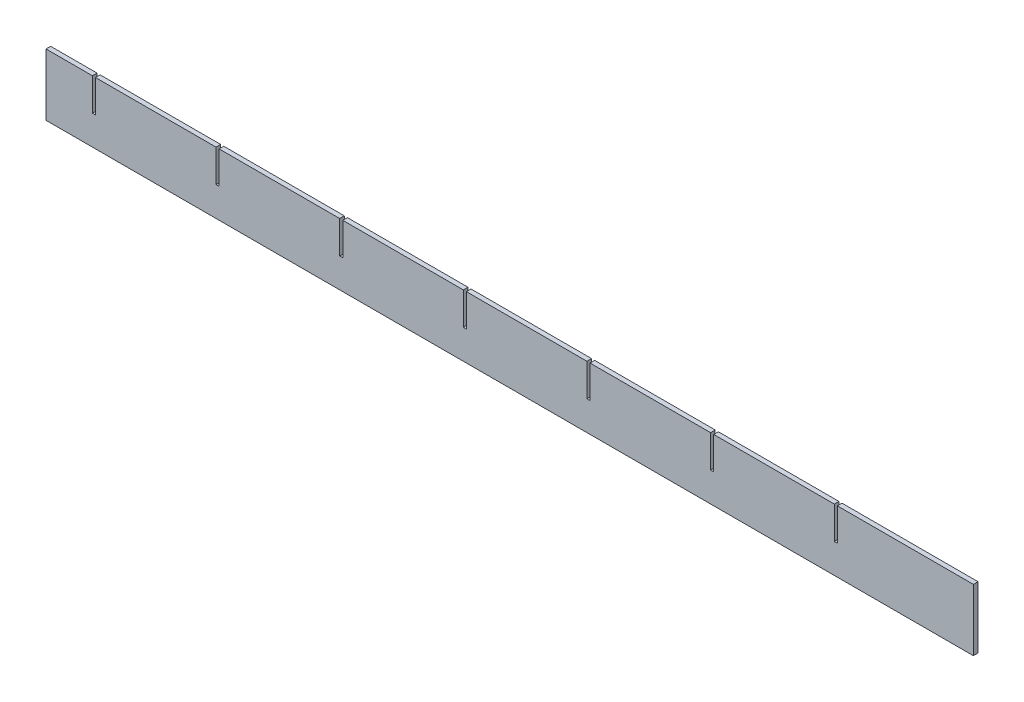
SolidWorks part; units mm, degrees
ref_plane "Front Plane" through (0, 0, 0) normal (0, 0, 1) x (1, 0, 0)
ref_plane "Top Plane" through (0, 0, 0) normal (0, 1, 0) x (1, 0, 0)
ref_plane "Right Plane" through (0, 0, 0) normal (1, 0, 0) x (0, 0, -1)
sketch "Sketch1" plane through (0, 0, 0) normal (0, 0, 1) x (1, 0, 0)
  line L0 (-190, 20) -> (-190, -1)
  line L1 (-300, 20) -> (-270, 20)
  line L2 (-300, 20) -> (-300, -20)
  line L3 (-300, -20) -> (300, -20)
  line L4 (300, 20) -> (300, -20)
  line L5 (-300, 20) -> (300, -20) construction
  line L6 (-300, -20) -> (300, 20) construction
  line L7 (-270, 20) -> (-268, 20) construction
  line L8 (-270, 20) -> (-270, -1)
  line L9 (-270, -1) -> (-268, -1)
  line L10 (-268, 20) -> (-268, -1)
  line L11 (-190, -1) -> (-188, -1)
  line L12 (-188, 20) -> (-188, -1)
  line L13 (-110, 20) -> (-110, -1)
  line L14 (-110, -1) -> (-108, -1)
  line L15 (-108, 20) -> (-108, -1)
  line L16 (-30, 20) -> (-30, -1)
  line L17 (-30, -1) -> (-28, -1)
  line L18 (-28, 20) -> (-28, -1)
  line L19 (50, 20) -> (50, -1)
  line L20 (50, -1) -> (52, -1)
  line L21 (52, 20) -> (52, -1)
  line L22 (130, 20) -> (130, -1)
  line L23 (130, -1) -> (132, -1)
  line L24 (132, 20) -> (132, -1)
  line L25 (210, 20) -> (210, -1)
  line L26 (210, -1) -> (212, -1)
  line L27 (212, 20) -> (212, -1)
  line L28 (-268, 20) -> (-190, 20) construction
  line L29 (212, 20) -> (300, 20)
  line L30 (132, 20) -> (210, 20)
  line L31 (52, 20) -> (130, 20)
  line L32 (-28, 20) -> (50, 20)
  line L33 (-108, 20) -> (-30, 20)
  line L34 (-188, 20) -> (-110, 20)
  line L35 (-270, 20) -> (-268, 20) construction
  line L36 (-270, 20) -> (-268, 20) construction
  line L37 (-268, 20) -> (-190, 20)
  point P0 (0, 0)
  dimension "D1" = 600
  dimension "D2" = 40
  dimension "D3" = 2
  dimension "D4" = 30
  dimension "D5" = 21
  dimension "D7" = 80
  dimension "D6" = 7
extrude "Boss-Extrude1" add sketch "Sketch1" along normal blind 3 contours L37 L10 L9 L8 L1 L2 L3 L4 L29 L27 L26 L25 L30 L24 L23 L22 L31 L21 L20 L19 L32 L18 L17 L16 L33 L15 L14 L13 L34 L12 L11 L0
